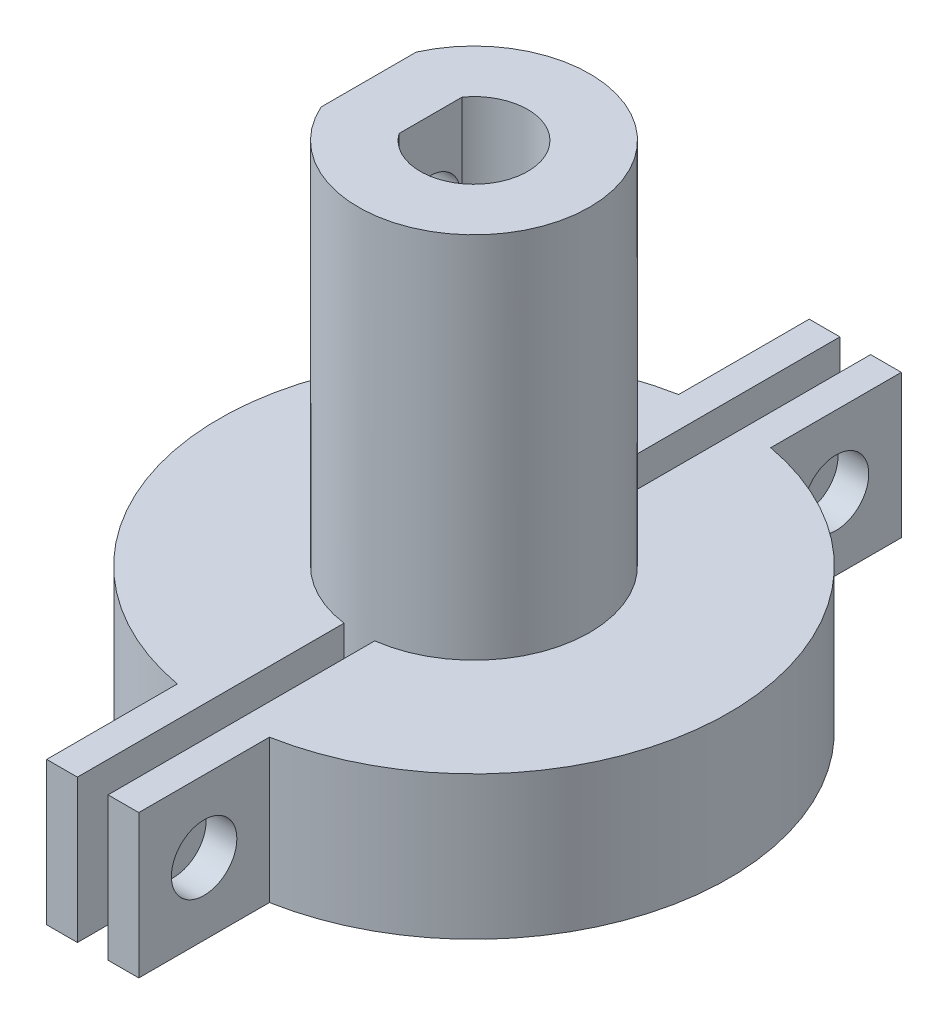
SolidWorks part; units mm, degrees
ref_plane "Front Plane" through (0, 0, 0) normal (0, 0, 1) x (1, 0, 0)
ref_plane "Top Plane" through (0, 0, 0) normal (0, 1, 0) x (1, 0, 0)
ref_plane "Right Plane" through (0, 0, 0) normal (1, 0, 0) x (0, 0, -1)
sketch "Sketch1" plane through (0, 0, 0) normal (0, 1, 0) x (1, 0, 0)
  line L0 (-2.1494, 1.55) -> (-2.1494, -1.55) construction
  line L1 (-5.1494, 2.3251) -> (-5.1494, -2.3251)
  line L2 (-2.1244, 1.5419) -> (-2.1244, -1.5419)
  arc A0 (-2.1494, -1.55) -> (-2.1494, 1.55) centre (0, 0) ccw construction
  arc A1 (-5.1494, -2.3251) -> (-5.1494, 2.3251) centre (0, 0) ccw
  arc A2 (-2.1244, -1.5419) -> (-2.1244, 1.5419) centre (0, 0) ccw
  dimension "D1" = 5.3
  dimension "D2" = 3.1
  dimension "D3" = 3
  dimension "D4" = 0.025
extrude "Boss-Extrude1" add sketch "Sketch1" along normal blind 18
sketch "Sketch2" plane through (0, 0, 0) normal (0, -1, 0) x (1, 0, 0)
  circle A0 centre (0, 0) radius 9.45
  circle A1 centre (0, 0) radius 12.45
  dimension "D1" = 18.9
  dimension "D2" = 3
extrude "Boss-Extrude2" add sketch "Sketch2" along normal blind 7 separate body
sketch "Sketch3" plane through (0, 0, 0) normal (0, -1, 0) x (1, 0, 0)
  circle A0 centre (0, 0) radius 12.45 construction
  circle A1 centre (0, 0) radius 12.45
extrude "Boss-Extrude3" add sketch "Sketch3" along normal blind 2
sketch "Sketch4" plane through (-5.1494, 0, 0) normal (-1, 0, 0) x (0, 0, 1)
  line L0 (0, 18) -> (0, 0) construction
  line L1 (-2.3251, 18) -> (2.3251, 18) construction
  line L2 (0, 9) -> (2.3251, 9) construction
  line L3 (2.3251, 18) -> (2.3251, 0) construction
  circle A0 centre (0, 14) radius 1.45
  circle A1 centre (0, 4) radius 1.45
  dimension "D1" = 2.9
  dimension "D2" = 2.9
  dimension "D3" = 10
extrude "Cut-Extrude1" cut sketch "Sketch4" against normal up to next
sketch "Sketch6" plane through (0, -7, 0) normal (0, -1, 0) x (1, 0, 0)
  line L0 (0, 0) -> (0, 12.45) construction
  line L1 (0, 0) -> (12.45, 0) construction
  line L2 (0.75, 9.4202) -> (0.75, 12.4274)
  line L3 (-0.75, 9.4202) -> (-0.75, 12.4274)
  line L4 (-0.75, 0) -> (-0.75, 12.45) construction
  line L5 (0.75, 0) -> (0.75, 12.45) construction
  line L6 (0.75, -9.4202) -> (0.75, -12.4274)
  line L7 (-0.75, -9.4202) -> (-0.75, -12.4274)
  circle A0 centre (0, 0) radius 12.45 construction
  circle A1 centre (0, 0) radius 9.45 construction
  arc A2 (-0.75, -9.4202) -> (0.75, -9.4202) centre (0, 0) ccw
  arc A3 (-0.75, -12.4274) -> (0.75, -12.4274) centre (0, 0) ccw
  arc A4 (0.75, 9.4202) -> (-0.75, 9.4202) centre (0, 0) ccw
  arc A5 (0.75, 12.4274) -> (-0.75, 12.4274) centre (0, 0) ccw
  dimension "D1" = 0.75
  dimension "D2" = 0.75
extrude "Cut-Extrude3" cut sketch "Sketch6" against normal up to next
sketch "Sketch7" plane through (0, -7, 0) normal (0, -1, 0) x (1, 0, 0)
  line L0 (-0.75, 12.4274) -> (-0.75, 18.6274)
  line L1 (-0.75, 18.6274) -> (-2.25, 18.6274)
  line L2 (-2.25, 18.6274) -> (-2.25, 12.245)
  line L3 (0, 0) -> (0, 12.45) construction
  line L4 (0, 0) -> (12.45, 0) construction
  line L5 (2.25, 18.6274) -> (2.25, 12.245)
  line L6 (0.75, 18.6274) -> (2.25, 18.6274)
  line L7 (0.75, 12.4274) -> (0.75, 18.6274)
  line L8 (0.75, -12.4274) -> (0.75, -18.6274)
  line L9 (0.75, -18.6274) -> (2.25, -18.6274)
  line L10 (2.25, -18.6274) -> (2.25, -12.245)
  line L11 (-2.25, -18.6274) -> (-2.25, -12.245)
  line L12 (-0.75, -18.6274) -> (-2.25, -18.6274)
  line L13 (-0.75, -12.4274) -> (-0.75, -18.6274)
  arc A0 (-0.75, 12.4274) -> (-0.75, -12.4274) centre (0, 0) ccw construction
  arc A2 (0.75, -12.4274) -> (0.75, 12.4274) centre (0, 0) ccw construction
  arc A7 (0.75, -12.4274) -> (2.25, -12.245) centre (0, 0) ccw
  arc A8 (-0.75, 12.4274) -> (-2.25, 12.245) centre (0, 0) ccw
  arc A9 (-2.25, -12.245) -> (-0.75, -12.4274) centre (0, 0) ccw
  arc A10 (2.25, 12.245) -> (0.75, 12.4274) centre (0, 0) ccw
  dimension "D1" = 6.2
  dimension "D2" = 1.5
extrude "Boss-Extrude5" add sketch "Sketch7" against normal up to surface (7 mm away) up to face at (0, 0, 0)
sketch "Sketch8" plane through (-2.25, 0, 0) normal (-1, 0, 0) x (0, 0, 1)
  line L0 (-15.4362, 0) -> (-15.4362, -3.5) construction
  line L1 (-18.6274, 0) -> (-12.245, 0) construction
  line L2 (-15.4362, -3.5) -> (-18.6274, -3.5) construction
  line L3 (-18.6274, 0) -> (-18.6274, -7) construction
  line L4 (0, 0) -> (0, -7) construction
  line L5 (-2.3251, 0) -> (2.3251, 0) construction
  line L6 (-12.245, -7) -> (12.245, -7) construction
  circle A0 centre (-15.4362, -3.5) radius 1.6
  circle A1 centre (15.4362, -3.5) radius 1.6
  dimension "D1" = 3.2
extrude "Cut-Extrude4" cut sketch "Sketch8" against normal through all
sketch "Sketch9" plane through (0, 0, 0) normal (0, 1, 0) x (1, 0, 0)
  line L0 (-0.75, -9.4202) -> (-0.75, -5.6)
  line L1 (0.75, -9.4202) -> (0.75, -5.6)
  line L2 (-0.75, 5.6) -> (-0.75, 9.4202)
  line L3 (0.75, 5.6) -> (0.75, 9.4202)
  arc A0 (-5.1494, -2.3251) -> (-5.1494, 2.3251) centre (0, 0) ccw construction
  arc A1 (-0.75, -5.6) -> (0.75, -5.6) centre (0, 0) ccw
  arc A2 (0.75, 9.4202) -> (-0.75, 9.4202) centre (0, 0) ccw construction
  arc A3 (0.75, 9.4202) -> (-0.75, 9.4202) centre (0, 0) ccw
  arc A4 (-0.75, -9.4202) -> (0.75, -9.4202) centre (0, 0) ccw construction
  arc A5 (-0.75, -9.4202) -> (0.75, -9.4202) centre (0, 0) ccw
  arc A6 (0.75, 5.6) -> (-0.75, 5.6) centre (0, 0) ccw
extrude "Cut-Extrude5" cut sketch "Sketch9" against normal through all contours L2 A3 L3 A6
